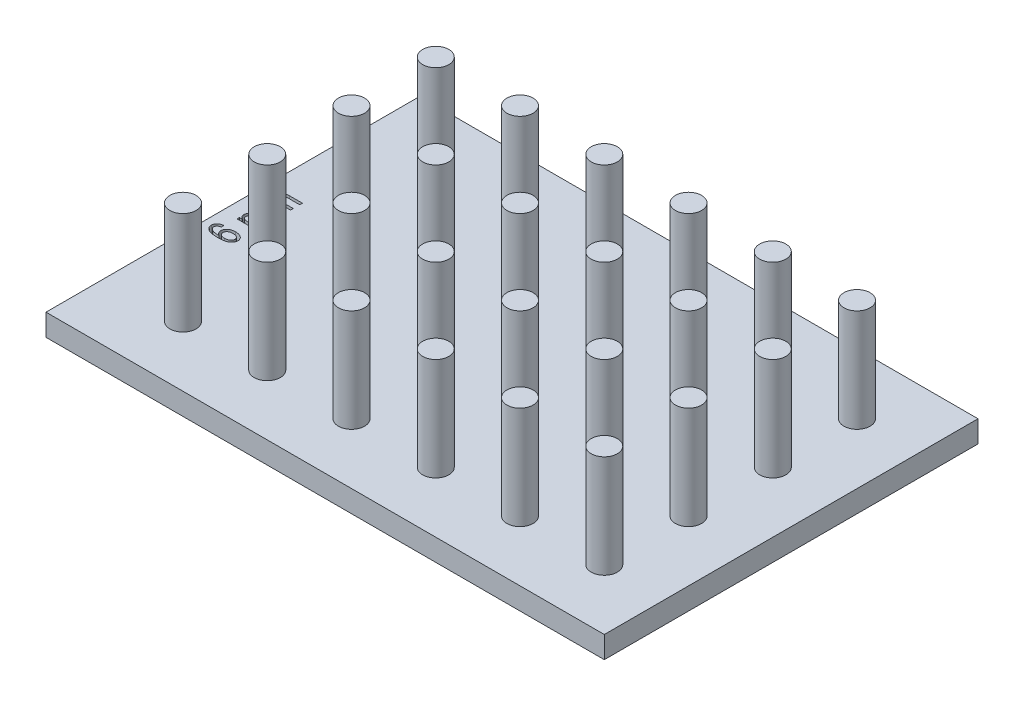
SolidWorks part; units mm, degrees
material "PVC Rigid"
ref_plane "Front Plane" through (0, 0, 0) normal (0, 0, 1) x (1, 0, 0)
ref_plane "Top Plane" through (0, 0, 0) normal (0, 1, 0) x (1, 0, 0)
ref_plane "Right Plane" through (0, 0, 0) normal (1, 0, 0) x (0, 0, -1)
ref_plane "Top of 24 well plate" through (0, 6, 0) normal (0, 1, 0) x (1, 0, 0)
ref_plane "Bottom of 24 well plate" through (0, 23.5, 0) normal (0, 1, 0) x (1, 0, 0)
sketch "Sketch1" plane through (0, 0, 0) normal (0, 1, 0) x (1, 0, 0)
  line L1 (-63.945, 42.8) -> (63.945, 42.8)
  line L2 (-63.945, 42.8) -> (-63.945, -42.8)
  line L3 (-63.945, -42.8) -> (63.945, -42.8)
  line L4 (63.945, 42.8) -> (63.945, -42.8)
  line L5 (-63.945, 42.8) -> (63.945, -42.8) construction
  line L6 (-63.945, -42.8) -> (63.945, 42.8) construction
  point P0 (0, 0)
  dimension "D1" = 127.89
  dimension "D2" = 85.6
ref_plane "Middle of 24 well plate" through (0, 14.75, 0) normal (0, 1, 0) x (1, 0, 0)
sketch "Wells_LSP" plane through (0, 0, 0) normal (0, 1, 0) x (1, 0, 0)
  line L0 (-46.425, 28.96) -> (-27.125, 28.96) construction
  line L1 (-63.945, 42.8) -> (63.945, 42.8) construction
  line L2 (-63.945, 42.8) -> (-63.945, -42.8) construction
  circle A0 centre (-46.425, 28.96) radius 7.81
  circle A1 centre (-27.125, 28.96) radius 7.81
  circle A2 centre (-7.825, 28.96) radius 7.81
  circle A3 centre (11.475, 28.96) radius 7.81
  circle A4 centre (30.775, 28.96) radius 7.81
  circle A5 centre (50.075, 28.96) radius 7.81
  circle A6 centre (-27.125, 9.66) radius 7.81
  circle A7 centre (-7.825, 9.66) radius 7.81
  circle A8 centre (11.475, 9.66) radius 7.81
  circle A9 centre (30.775, 9.66) radius 7.81
  circle A10 centre (50.075, 9.66) radius 7.81
  circle A11 centre (-27.125, -9.64) radius 7.81
  circle A12 centre (-7.825, -9.64) radius 7.81
  circle A13 centre (11.475, -9.64) radius 7.81
  circle A14 centre (30.775, -9.64) radius 7.81
  circle A15 centre (50.075, -9.64) radius 7.81
  circle A16 centre (-27.125, -28.94) radius 7.81
  circle A17 centre (-7.825, -28.94) radius 7.81
  circle A18 centre (11.475, -28.94) radius 7.81
  circle A19 centre (30.775, -28.94) radius 7.81
  circle A20 centre (50.075, -28.94) radius 7.81
  circle A21 centre (-46.425, 9.66) radius 7.81
  circle A22 centre (-46.425, -9.64) radius 7.81
  circle A23 centre (-46.425, -28.94) radius 7.81
  dimension "D2" = 6
  dimension "D4" = 4
  dimension "D7" = 15.62
  dimension "D3" = 19.3
  dimension "D5" = 13.84
  dimension "D6" = 17.52
ref_plane "Plane1" through (0, 0, -28.96) normal (0, 0, 1) x (1, 0, 0)
sketch "Sketch2" plane through (0, 0, -28.96) normal (0, 0, 1) x (1, 0, 0)
  line L0 (50.075, 14.75) -> (50.075, 0) construction
  line L1 (50.075, 23.5) -> (53.075, 23.5)
  line L2 (50.075, 23.5) -> (50.075, 0)
  line L3 (50.075, 0) -> (53.075, 0)
  line L4 (53.075, 23.5) -> (53.075, 0)
  line L5 (55, 6) -> (-55, 6) construction
  line L7 (55, 23.5) -> (-55, 23.5) construction
  line L8 (55, 14.75) -> (-55, 14.75) construction
  line L10 (-63.945, 0) -> (63.945, 0) construction
  point P6 (0, 0)
  point P10 (53.075, 6)
  point P13 (50.075, 14.75)
  dimension "D1" = 0
  dimension "D2" = 3
revolve "Revolve1" add sketch "Sketch2" angle 360 about L2
extrude "Boss-Extrude2" add sketch "Sketch1" against normal blind 5
pattern_linear "LPattern2" count 4 spacing 19.3 along (0, 0, 1) count 6 spacing 19.3 along (-1, 0, 0) of "Revolve1"
sketch "Sketch5" plane through (0, 0, 0) normal (0, 1, 0) x (1, 0, 0)
  line L0 (-56.1948, 42.8) -> (-56.1948, -42.8) construction
  line L1 (63.945, 42.8) -> (-63.945, 42.8) construction
  line L2 (-63.945, -42.8) -> (63.945, -42.8) construction
  text T0 "6 mm" font "Arial Narrow" height 6
extrude "Cut-Extrude1" cut sketch "Sketch5" against normal blind 2
equation "\"D1\"= 0.32"
equation "\"D1\"= 1.27 - 0.32"
